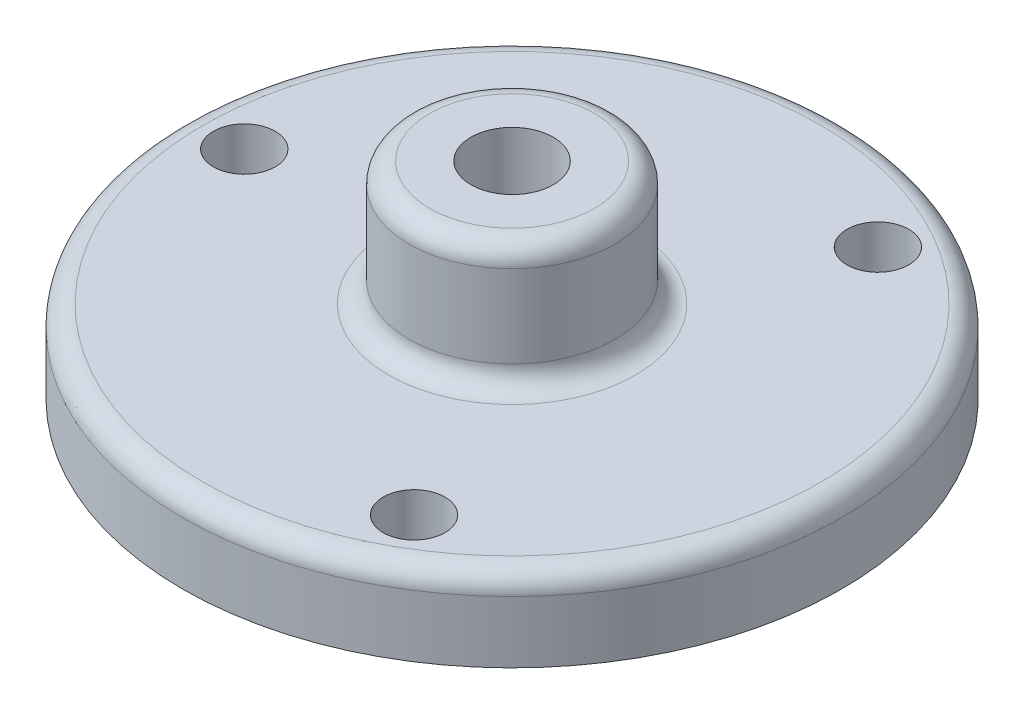
SolidWorks part; units mm, degrees
ref_plane "Front Plane" through (0, 0, 0) normal (0, 0, 1) x (1, 0, 0)
ref_plane "Top Plane" through (0, 0, 0) normal (0, 1, 0) x (1, 0, 0)
ref_plane "Right Plane" through (0, 0, 0) normal (1, 0, 0) x (0, 0, -1)
sketch "Sketch1" plane through (0, 0, 0) normal (0, 1, 0) x (1, 0, 0)
  circle A0 centre (0, 0) radius 16
  dimension "D1" = 32
extrude "Boss-Extrude1" add sketch "Sketch1" along normal blind 4
sketch "Sketch2" plane through (0, 4, 0) normal (0, 1, 0) x (1, 0, 0)
  circle A0 centre (0, 0) radius 5
  circle A1 centre (0, 0) radius 16 construction
  dimension "D1" = 10
extrude "Boss-Extrude2" add sketch "Sketch2" along normal blind 6
sketch "Sketch3" plane through (0, 4, 0) normal (0, 1, 0) x (1, 0, 0)
  circle A0 centre (0, 0) radius 13 construction
  circle A1 centre (-13, 0) radius 1.5
  circle A2 centre (6.5, 11.2583) radius 1.5
  circle A3 centre (6.5, -11.2583) radius 1.5
  circle A4 centre (0, 0) radius 5 construction
  point P11 (0, 0)
  dimension "D1" = 3
  dimension "D2" = 3
  dimension "D5" = 26
extrude "Cut-Extrude1" cut sketch "Sketch3" against normal up to next
sketch "Sketch4" plane through (0, 0, 0) normal (0, -1, 0) x (1, 0, 0)
  circle A0 centre (0, 0) radius 8
  dimension "D1" = 16
extrude "Boss-Extrude3" add sketch "Sketch4" along normal blind 1
fillet "Fillet1" radius 1 3 edges at (0, 4, 16) (0, 10, 5) (0, 4, 5)
sketch "Sketch5" plane through (0, 10, 0) normal (0, 1, 0) x (1, 0, 0)
  circle A0 centre (0, 0) radius 2
  circle A1 centre (0, 0) radius 4 construction
  dimension "D1" = 4
extrude "Cut-Extrude2" cut sketch "Sketch5" against normal through all both and the other way through all
